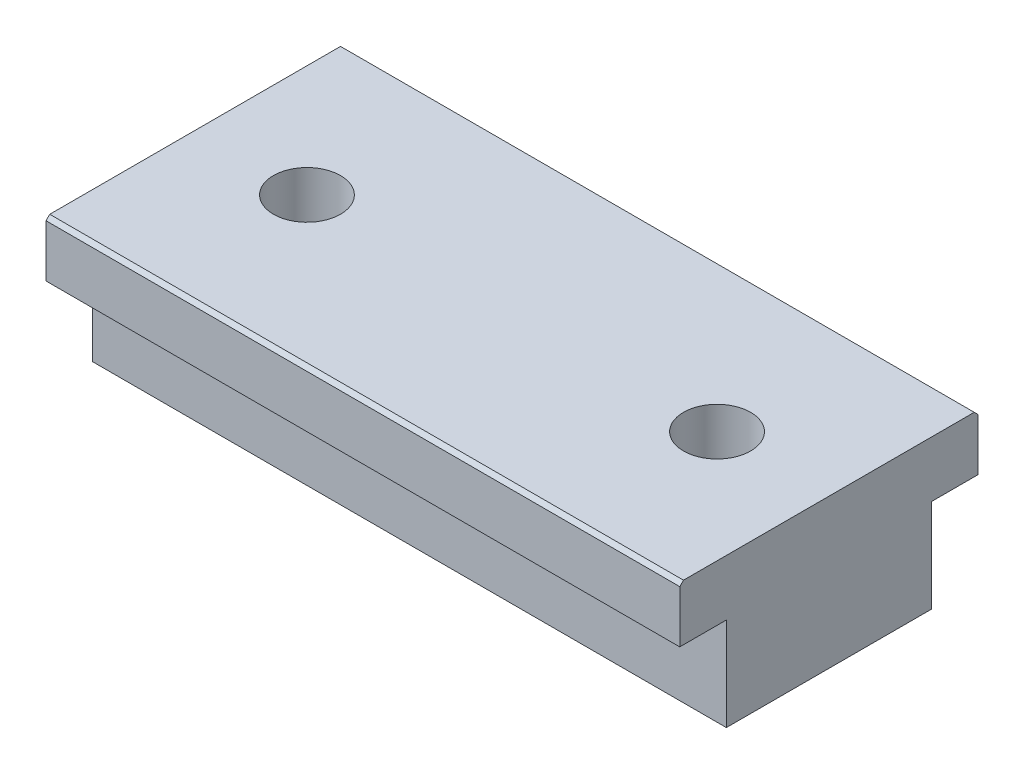
SolidWorks part; units mm, degrees
ref_plane "前视基准面" through (0, 0, 0) normal (0, 0, 1) x (1, 0, 0)
ref_plane "上视基准面" through (0, 0, 0) normal (0, 1, 0) x (1, 0, 0)
ref_plane "右视基准面" through (0, 0, 0) normal (1, 0, 0) x (0, 0, -1)
sketch "草图2" plane through (0, 0, 0) normal (1, 0, 0) x (0, 0, -1)
  line L0 (0, 0) -> (80, 0)
  line L1 (80, 0) -> (80, -15)
  line L2 (80, -15) -> (67.5, -15)
  line L3 (67.5, -15) -> (67.5, -40)
  line L4 (67.5, -40) -> (12.5, -40)
  line L5 (12.5, -40) -> (12.5, -15)
  line L6 (12.5, -15) -> (0, -15)
  line L7 (0, -15) -> (0, 0)
  line L8 (40, 0) -> (40, -114.4538) construction
  dimension "D1" = 80
  dimension "D2" = 55
  dimension "D3" = 15
  dimension "D4" = 40
extrude "凸台-拉伸1" add sketch "草图2" along normal blind 170
hole_wizard "孔1" positions "3D草图1" profile "草图3" legacy end condition through all
sketch3d "3D草图1"
  line L0 (0, 0, -80) -> (0, 0, 0) construction
  line L1 (0, 0, -40) -> (170, 0, -40) construction
  line L2 (170, 0, -80) -> (170, 0, 0) construction
  point P0 (30, 0, -40)
  point P2 (140, 0, -40)
  point P12 (0, 0, 0)
  dimension "D1" = 30
  dimension "D2" = 110
sketch "草图3" plane through (30, 0, -40) normal (1, 0, 0) x (0, 0, 1)
  line L0 (0, 0) -> (0, 40)
  line L1 (0, 40) -> (5.5, 40)
  line L2 (5.5, 40) -> (5.5, 15)
  line L3 (5.5, 15) -> (9, 15)
  line L4 (9, 15) -> (9, 0)
  line L5 (9, 0) -> (0, 0)
  line L6 (0, 110) -> (0, -10) construction
  dimension "直径" = 11
  dimension "深度" = 40
  dimension "柱坑直径" = 18
  dimension "柱坑深度" = 15
chamfer "倒角1" distance 1 2 edges at (85, 0, -80) (85, 0, 0)
